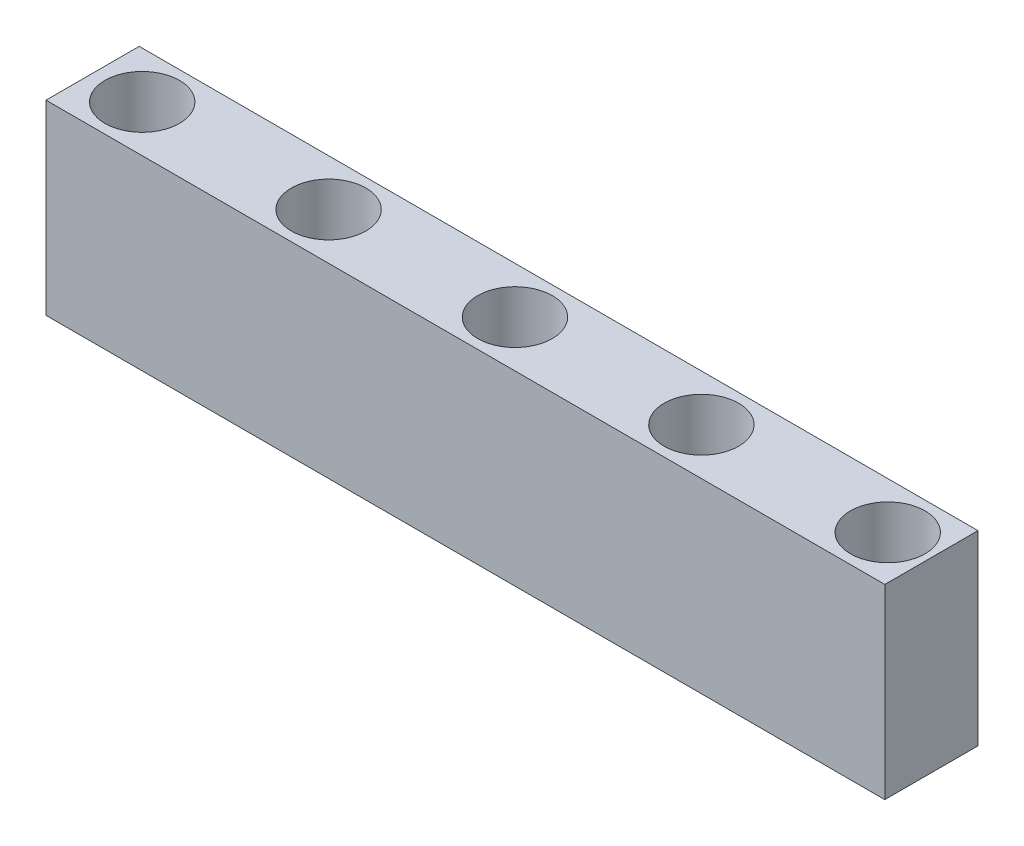
SolidWorks part; units mm, degrees
material "3.1355 (EN-AW 2024)"
ref_plane "前视基准面" through (0, 0, 0) normal (0, 0, 1) x (1, 0, 0)
ref_plane "上视基准面" through (0, 0, 0) normal (0, 1, 0) x (1, 0, 0)
ref_plane "右视基准面" through (0, 0, 0) normal (1, 0, 0) x (0, 0, -1)
sketch "草图1" plane through (0, 0, 0) normal (0, 1, 0) x (1, 0, 0)
  line L1 (-40, 2.5) -> (10, 2.5)
  line L2 (-40, 2.5) -> (-40, -2.5)
  line L3 (-40, -2.5) -> (10, -2.5)
  line L4 (10, 2.5) -> (10, -2.5)
  circle A1 centre (-37.3382, 0) radius 2
  circle A2 centre (-27.3382, 0) radius 2
  circle A3 centre (-17.3382, 0) radius 2
  circle A4 centre (-7.3382, 0) radius 2
  circle A5 centre (2.6618, 0) radius 2
  point P0 (0, 0)
  dimension "D3" = 5
  dimension "D1" = 5
  dimension "D2" = 50
extrude "凸台-拉伸1" add sketch "草图1" along normal blind 10
sketch "草图2" plane through (0, 10, 0) normal (0, 1, 0) x (1, 0, 0)
  line L0 (5.0039, 2.5) -> (5.0039, -2.5)
  line L1 (10, 2.5) -> (-40, 2.5) construction
  line L2 (-40, -2.5) -> (10, -2.5) construction
  line L3 (5.0039, 2.5) -> (10, 2.5)
  line L4 (10, 2.5) -> (10, -2.5)
  line L5 (10, -2.5) -> (5.0039, -2.5)
extrude "切除-拉伸1" cut sketch "草图2" against normal blind 10
